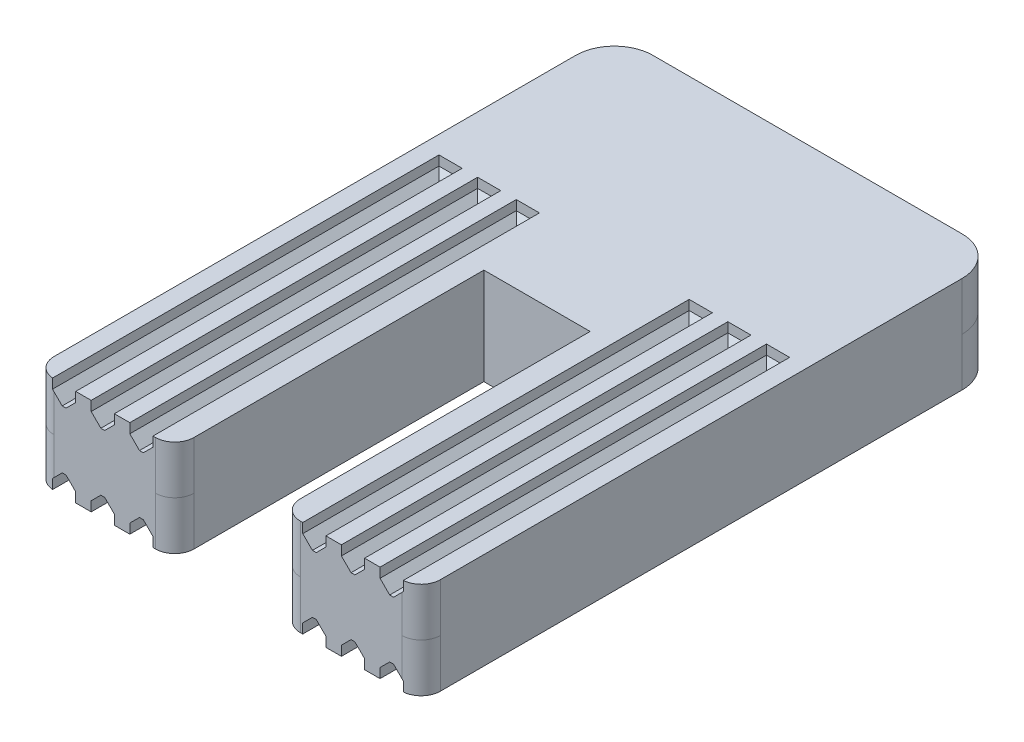
SolidWorks part; units mm, degrees
ref_plane "Plano frontal" through (0, 0, 0) normal (0, 0, 1) x (1, 0, 0)
ref_plane "Plano superior" through (0, 0, 0) normal (0, 1, 0) x (1, 0, 0)
ref_plane "Plano direito" through (0, 0, 0) normal (1, 0, 0) x (0, 0, -1)
sketch "Esboço1" plane through (0, 0, 0) normal (0, 1, 0) x (1, 0, 0)
  line L1 (-10, 15) -> (10, 15)
  line L2 (-10, 15) -> (-10, -15)
  line L3 (-10, -15) -> (10, -15)
  line L4 (10, 15) -> (10, -15)
  line L5 (-10, 15) -> (10, -15) construction
  line L6 (-10, -15) -> (10, 15) construction
  point P0 (0, 0)
  dimension "D1" = 30
  dimension "D2" = 20
extrude "Ressalto-extrusão1" add sketch "Esboço1" along normal blind 2.5
sketch "Esboço2" plane through (0, 2.5, 0) normal (0, 1, 0) x (1, 0, 0)
  line L0 (0, 14.0771) -> (0, -13.776) construction
  line L1 (-10, -15) -> (10, -15) construction
  line L2 (-2.75, 1) -> (2.75, 1)
  line L3 (-2.75, 1) -> (-2.75, -15)
  line L4 (-2.75, -15) -> (2.75, -15)
  line L5 (2.75, 1) -> (2.75, -15)
  line L6 (-2.75, 1) -> (2.75, -15) construction
  line L7 (-2.75, -15) -> (2.75, 1) construction
  point P3 (0, -7)
  dimension "D1" = 5.5
  dimension "D2" = 16
extrude "Corte-extrusão1" cut sketch "Esboço2" against normal blind 5
fillet "Filete1" radius 1 1 edges at (10, 1.25, 15)
fillet "Filete2" radius 2 1 edges at (10, 1.25, -15)
fillet "Filete3" radius 2 1 edges at (-10, 1.25, -15)
fillet "Filete4" radius 1 1 edges at (-10, 1.25, 15)
fillet "Filete5" radius 1 1 edges at (-2.75, 1.25, 15)
fillet "Filete6" radius 1 1 edges at (2.75, 1.25, 15)
sketch "Esboço3" plane through (0, 2.5, 0) normal (0, 1, 0) x (1, 0, 0)
  line L0 (0, 15.7458) -> (0, -17.1259) construction
  line L1 (-9, -15) -> (-3.75, -15) construction
  line L2 (-5.075, 5) -> (-3.875, 5)
  line L3 (-5.075, 5) -> (-5.075, -15)
  line L4 (-5.075, -15) -> (-3.875, -15)
  line L5 (-3.875, 5) -> (-3.875, -15)
  line L6 (-5.075, 5) -> (-3.875, -15) construction
  line L7 (-5.075, -15) -> (-3.875, 5) construction
  line L8 (-2.75, 1) -> (-2.75, -14) construction
  line L9 (-7.075, 5) -> (-5.875, 5)
  line L10 (-7.075, 5) -> (-7.075, -15)
  line L11 (-7.075, -15) -> (-5.875, -15)
  line L12 (-5.875, 5) -> (-5.875, -15)
  line L13 (-7.075, 5) -> (-5.875, -15) construction
  line L14 (-7.075, -15) -> (-5.875, 5) construction
  line L16 (-9.075, 5) -> (-7.875, 5)
  line L17 (-9.075, 5) -> (-9.075, -15)
  line L18 (-9.075, -15) -> (-7.875, -15)
  line L19 (-7.875, 5) -> (-7.875, -15)
  line L20 (-9.075, 5) -> (-7.875, -15) construction
  line L21 (-9.075, -15) -> (-7.875, 5) construction
  point P3 (-4.475, -5)
  point P10 (-6.475, -5)
  point P17 (-8.475, -5)
  dimension "D1" = 1.2
  dimension "D2" = 1.725
  dimension "D3" = 1.2
  dimension "D4" = 20
  dimension "D5" = 20
  dimension "D6" = 2
  dimension "D7" = 20
  dimension "D8" = 1.2
  dimension "D9" = 2
extrude "Corte-extrusão2" cut sketch "Esboço3" against normal blind 1
chamfer "Chanfro1" distance 0.5 angle 45 9 edges at (-7.875, 1.5, 5) (-9.075, 1.5, 4.9986) (-3.875, 1.5, 5) (-4.475, 1.5, -5) (-5.075, 1.5, 5) (-5.875, 1.5, 5) (-6.475, 1.5, -5) (-7.075, 1.5, 5) (-8.475, 1.5, -5)
mirror "Espelhar4" about plane through (0, 0, 0) normal (1, 0, 0) of "Corte-extrusão2"
chamfer "Chanfro3" distance 0.5 angle 45 9 edges at (9.075, 1.5, 4.9986) (8.475, 1.5, -5) (7.875, 1.5, 5) (7.075, 1.5, 5) (6.475, 1.5, -5) (5.875, 1.5, 5) (5.075, 1.5, 5) (4.475, 1.5, -5) (3.875, 1.5, 5)
mirror "Espelhar5" about plane through (0, 0, 0) normal (0, 1, 0) of "Ressalto-extrusão1"
mirror "Espelhar6" about plane through (0, 0, 0) normal (0, 1, 0) of "Corte-extrusão2", "Filete1"
mirror "Espelhar7" about plane through (0, 0, 0) normal (0, 1, 0) of "Espelhar4"
fillet "Filete7" radius 2 3 edges at (9, 0, -15) (10, 0, -14) (10, -1.25, -15)
fillet "Filete8" radius 2 3 edges at (-10, 0, -14) (-9, 0, -15) (-10, -1.25, -15)
fillet "Filete9" radius 1 5 edges at (-9.5, 0, 15) (-10, 0, 14.5) (-9.5375, -2.5, 15) (-10, -1.25, 15) (-9.075, -2, 15)
chamfer "Chanfro4" distance 0.5 angle 45 9 edges at (3.875, -1.5, 5) (4.475, -1.5, -5) (5.075, -1.5, 5) (5.875, -1.5, 5) (6.475, -1.5, -5) (7.075, -1.5, 5) (7.875, -1.5, 5) (8.475, -1.5, -5) (9.075, -1.5, 4.9986)
chamfer "Chanfro5" distance 0.5 angle 45 9 edges at (-9.075, -1.5, 4.9986) (-8.475, -1.5, -5) (-7.875, -1.5, 5) (-7.075, -1.5, 5) (-6.475, -1.5, -5) (-5.875, -1.5, 5) (-5.075, -1.5, 5) (-4.475, -1.5, -5) (-3.875, -1.5, 5)
mirror "Espelhar8" about plane through (0, 0, 0) normal (0, 1, 0) of "Corte-extrusão1"
fillet "Filete10" radius 1 3 edges at (3.25, 0, 15) (2.75, 0, 14.5) (2.75, -1.25, 15)
fillet "Filete11" radius 1 3 edges at (-3.25, 0, 15) (-2.75, 0, 14.5) (-2.75, -1.25, 15)
